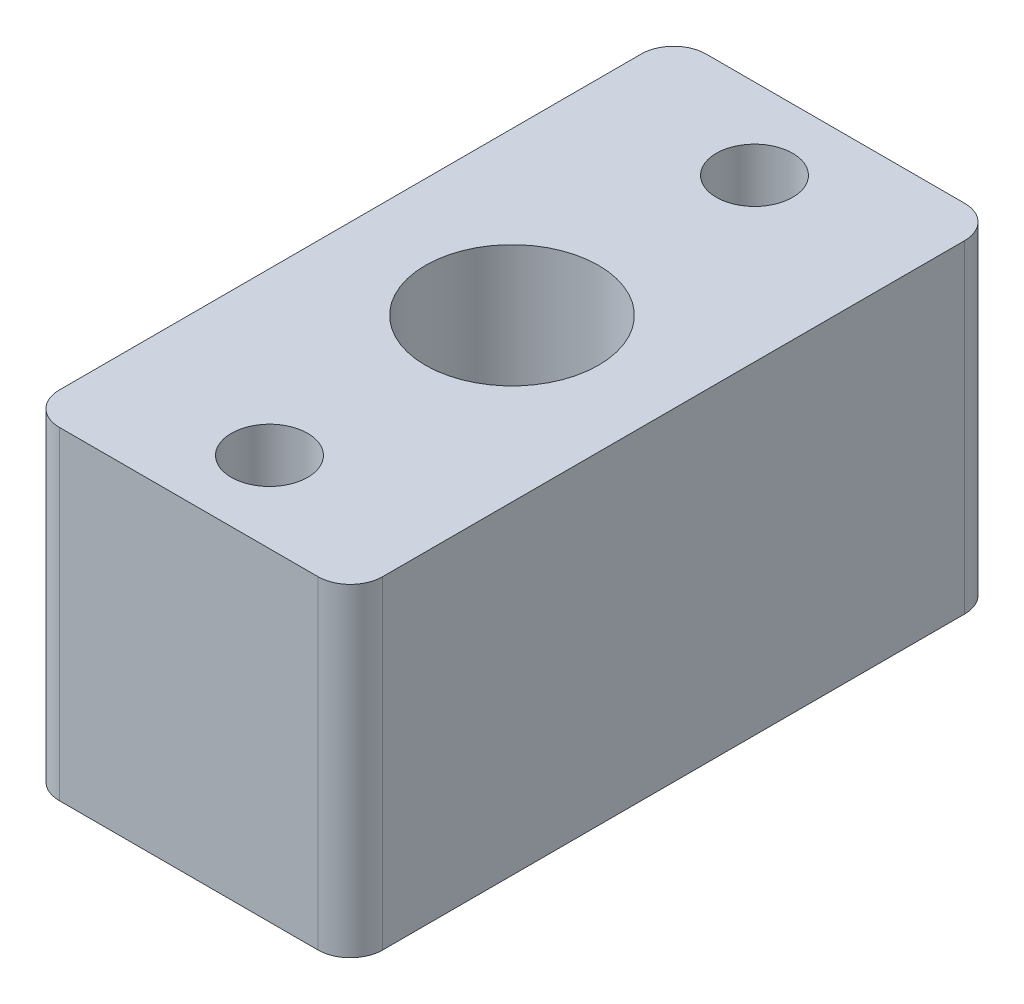
SolidWorks part; units mm, degrees
ref_plane "Front Plane" through (0, 0, 0) normal (0, 0, 1) x (1, 0, 0)
ref_plane "Top Plane" through (0, 0, 0) normal (0, 1, 0) x (1, 0, 0)
ref_plane "Right Plane" through (0, 0, 0) normal (1, 0, 0) x (0, 0, -1)
sketch "Sketch2" plane through (0.748, -17998.4934, -0.2119) normal (0, -1, 0) x (1, 0, 0)
  line L1 (9.2173, -483.0751) -> (-3.4827, -483.0751)
  line L2 (9.2173, -483.0751) -> (9.2173, -508.4751)
  line L3 (9.2173, -508.4751) -> (-3.4827, -508.4751)
  line L4 (-3.4827, -483.0751) -> (-3.4827, -508.4751)
  circle A0 centre (2.8673, -495.7751) radius 3.5
  circle A1 centre (2.8673, -486.2501) radius 1.5
  circle A4 centre (2.8673, -505.3001) radius 1.5
  point P0 (2.8673, -495.7751)
  dimension "D1" = 12.7
  dimension "D13" = 7
  dimension "D14" = 3
  dimension "D16" = 3
  dimension "D2" = 25.4
  dimension "D5" = 6.35
  dimension "D6" = 6.35
  dimension "D7" = 3.175
  dimension "D10" = 3.175
  dimension "D11" = 12.7
  dimension "D12" = 6.35
extrude "Boss-Extrude1" add sketch "Sketch2" along normal blind 12.7 contours L3 L4 L1 L2
fillet "Fillet1" radius 1.27 4 edges at (-2.7411, -18004.8379, -483.287) (-2.7414, -18004.8376, -508.687) (9.9586, -18004.8371, -508.6872) (9.9589, -18004.8374, -483.2872)
hole_wizard "M8 Tapped Hole1" positions "Sketch4" profile "Sketch3" tap size "M8" standard "ISO"
sketch "Sketch4" plane through (0.748, -17998.4934, -0.2119) normal (0, 1, 0) x (1, 0, 0)
  point P0 (2.8605, 495.7751)
sketch "Sketch3" plane through (3.6085, -17998.4875, -495.987) normal (0.7071, 0, 0.7071) x (-0.7071, 0, 0.7071)
  line L0 (0, 0) -> (0, 24.3949)
  line L1 (0, 24.3949) -> (3.4, 22.352)
  line L2 (3.4, 22.352) -> (3.4, 0)
  line L5 (3.4, 0) -> (0, 0)
  line L10 (0, 24.3949) -> (-3.4, 22.352) construction
  line L11 (0, -6.35) -> (0, 107.95) construction
  dimension "Tap Drill Dia." = 6.8
  dimension "Tap Drill Depth" = 22.352
  dimension "Drill Angle" = 118
cosmetic thread "Hole Thread1" parameters "D1"=12.7, "D2"=8
hole_wizard "Ø3.0 (3) Diameter Hole1" positions "Sketch6" profile "Sketch5" hole size "Ø3.0" standard "ANSI Metric" end condition through all
sketch "Sketch6" plane through (0.748, -17998.4934, -0.2119) normal (0, 1, 0) x (1, 0, 0)
  point P0 (2.8606, 486.2501)
  point P3 (2.8604, 505.3001)
sketch "Sketch5" plane through (3.6086, -17998.4876, -486.462) normal (0.7071, 0, 0.7071) x (-0.7071, 0, 0.7071)
  line L0 (0, 0) -> (0, 12.7008)
  line L1 (0, 12.7008) -> (1.5, 12.7008)
  line L2 (1.5, 12.7008) -> (1.5, 0)
  line L5 (1.5, 0) -> (0, 0)
  line L11 (0, -6.35) -> (0, 107.95) construction
  dimension "Thru Hole Dia." = 3
  dimension "Thru Hole Depth" = 12.7008
